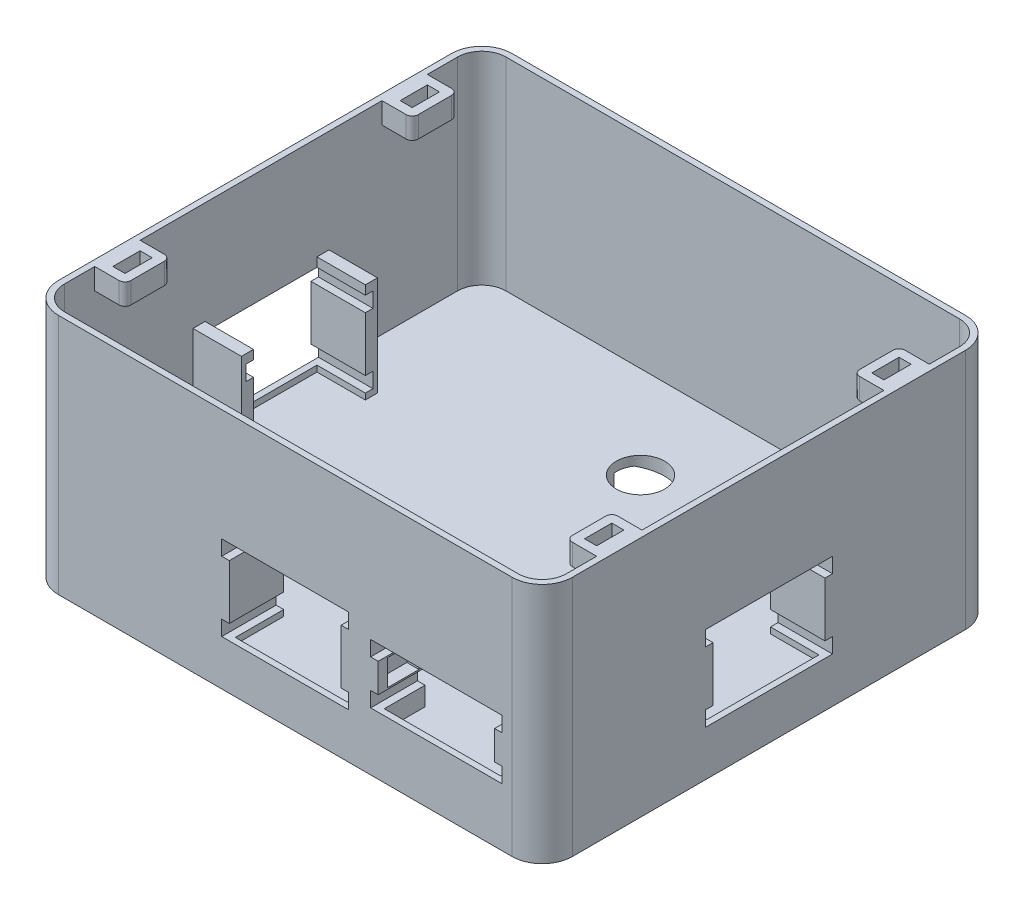
SolidWorks part; units mm, degrees
ref_plane "Front Plane" through (0, 0, 0) normal (0, 0, 1) x (1, 0, 0)
ref_plane "Top Plane" through (0, 0, 0) normal (0, 1, 0) x (1, 0, 0)
ref_plane "Right Plane" through (0, 0, 0) normal (1, 0, 0) x (0, 0, -1)
sketch "Sketch2" plane through (0, 0, 0) normal (0, 1, 0) x (1, 0, 0)
  line L1 (-85, 75) -> (85, 75)
  line L2 (-85, 75) -> (-85, -75)
  line L3 (-85, -75) -> (85, -75)
  line L4 (85, 75) -> (85, -75)
  line L5 (-85, 75) -> (85, -75) construction
  line L6 (-85, -75) -> (85, 75) construction
  point P0 (0, 0)
  dimension "D1" = 170
  dimension "D2" = 150
extrude "Boss-Extrude1" add sketch "Sketch2" along normal blind 80
fillet "Fillet1" radius 10 4 edges at (-85, 40, -75) (85, 40, -75) (85, 40, 75) (-85, 40, 75)
shell "Shell1" thickness 2
sketch "Sketch5" plane through (0, 0, 75) normal (0, 0, 1) x (1, 0, 0)
  line L1 (-18.5, 43) -> (18.5, 43)
  line L2 (-18.5, 43) -> (-18.5, 15)
  line L3 (-18.5, 15) -> (18.5, 15)
  line L4 (18.5, 43) -> (18.5, 15)
  line L5 (-18.5, 43) -> (-21, 43)
  line L6 (-21, 43) -> (-21, 38)
  line L7 (-21, 38) -> (-18.5, 38)
  line L8 (-18.5, 38) -> (-18.5, 43)
  line L9 (0, 43) -> (0, 15) construction
  line L10 (-18.5, 29) -> (18.5, 29) construction
  line L11 (-21, 20) -> (-18.5, 20)
  line L12 (-21, 15) -> (-21, 20)
  line L13 (-18.5, 15) -> (-21, 15)
  line L14 (-18.5, 20) -> (-18.5, 15)
  line L15 (21, 15) -> (21, 20)
  line L16 (18.5, 15) -> (21, 15)
  line L17 (18.5, 20) -> (18.5, 15)
  line L18 (21, 20) -> (18.5, 20)
  line L19 (21, 38) -> (18.5, 38)
  line L20 (21, 43) -> (21, 38)
  line L21 (18.5, 43) -> (21, 43)
  line L22 (18.5, 38) -> (18.5, 43)
  line L23 (-75, 13) -> (75, 13) construction
  point P4 (0, 15)
  dimension "D1" = 37
  dimension "D2" = 28
  dimension "D3" = 5
  dimension "D7" = 2.5
  dimension "D8" = 2
extrude "Cut-Extrude1" cut sketch "Sketch5" against normal up to surface (2 mm away) contours L1 L4 L3 L2 | L7 L8 L5 L6 | L12 L11 L14 L13 | L20 L19 L22 L21 | L15 L18 L17 L16 up to face at (0, 46.5, 73)
sketch "Sketch6" plane through (0, 0, 73) normal (0, 0, -1) x (-1, 0, 0)
  line L0 (18.5, 13) -> (22.5, 13)
  line L2 (-22.5, 46) -> (-22.5, 13)
  line L4 (21, 43) -> (18.5, 43)
  line L5 (21, 38) -> (21, 43)
  line L6 (18.5, 38) -> (21, 38)
  line L7 (18.5, 43) -> (18.5, 38)
  line L8 (21, 43) -> (18.5, 43)
  line L9 (21, 38) -> (21, 43)
  line L10 (18.5, 38) -> (21, 38)
  line L12 (18.5, 43) -> (-18.5, 43)
  line L13 (-18.5, 43) -> (-18.5, 15)
  line L14 (-18.5, 15) -> (18.5, 15)
  line L15 (18.5, 15) -> (18.5, 43)
  line L17 (-18.5, 46) -> (-18.5, 43)
  line L19 (18.5, 13) -> (18.5, 15)
  line L20 (-21, 38) -> (-18.5, 38)
  line L21 (-18.5, 38) -> (-18.5, 43)
  line L22 (-18.5, 43) -> (-21, 43)
  line L23 (-21, 43) -> (-21, 38)
  line L24 (-21, 38) -> (-18.5, 38)
  line L26 (-18.5, 43) -> (-21, 43)
  line L27 (-21, 43) -> (-21, 38)
  line L28 (-21, 20) -> (-21, 15)
  line L29 (-18.5, 20) -> (-21, 20)
  line L30 (-18.5, 15) -> (-18.5, 20)
  line L31 (-21, 15) -> (-18.5, 15)
  line L32 (-21, 20) -> (-21, 15)
  line L33 (-18.5, 20) -> (-21, 20)
  line L35 (-21, 15) -> (-18.5, 15)
  line L36 (21, 20) -> (18.5, 20)
  line L37 (18.5, 20) -> (18.5, 15)
  line L38 (18.5, 15) -> (21, 15)
  line L39 (21, 15) -> (21, 20)
  line L40 (21, 20) -> (18.5, 20)
  line L42 (18.5, 15) -> (21, 15)
  line L43 (21, 15) -> (21, 20)
  line L44 (22.5, 46) -> (22.5, 13)
  line L45 (-18.5, 13) -> (-22.5, 13)
  line L46 (-18.5, 38) -> (-18.5, 20)
  line L47 (18.5, 43) -> (18.5, 46)
  line L48 (18.5, 20) -> (18.5, 38)
  line L49 (-18.5, 15) -> (-18.5, 13)
  line L50 (22.5, 46) -> (18.5, 46)
  line L51 (-22.5, 46) -> (-18.5, 46)
  line L54 (21, 43) -> (-21, 43) construction
  line L55 (75, 13) -> (-75, 13) construction
  dimension "D6" = 3
  dimension "D7" = 4
  dimension "D8" = 4
  dimension "D1" = 0
  dimension "D2" = 0
  dimension "D3" = 0
  dimension "D4" = 0
  dimension "D5" = 0
extrude "Boss-Extrude2" add sketch "Sketch6" along normal blind 16
sketch "Sketch7" plane through (85, 0, 0) normal (1, 0, 0) x (0, 0, -1)
  line L0 (-65, 13) -> (65, 13) construction
  line L1 (-18.5, 43) -> (18.5, 43)
  line L2 (-18.5, 43) -> (-18.5, 15)
  line L3 (-18.5, 15) -> (18.5, 15)
  line L4 (18.5, 43) -> (18.5, 15)
  line L5 (-18.5, 43) -> (-21, 43)
  line L6 (-21, 43) -> (-21, 38)
  line L7 (-21, 38) -> (-18.5, 38)
  line L8 (-18.5, 38) -> (-18.5, 43)
  line L9 (0, 43) -> (0, 15) construction
  line L10 (-18.5, 29) -> (18.5, 29) construction
  line L11 (-21, 20) -> (-18.5, 20)
  line L12 (-21, 15) -> (-21, 20)
  line L13 (-18.5, 15) -> (-21, 15)
  line L14 (-18.5, 20) -> (-18.5, 15)
  line L15 (21, 15) -> (21, 20)
  line L16 (18.5, 15) -> (21, 15)
  line L17 (18.5, 20) -> (18.5, 15)
  line L18 (21, 20) -> (18.5, 20)
  line L19 (21, 38) -> (18.5, 38)
  line L20 (21, 43) -> (21, 38)
  line L21 (18.5, 43) -> (21, 43)
  line L22 (18.5, 38) -> (18.5, 43)
  dimension "D1" = 37
  dimension "D2" = 28
  dimension "D3" = 5
  dimension "D7" = 2.5
  dimension "D8" = 2
extrude "Cut-Extrude2" cut sketch "Sketch7" against normal blind 2 contours L1 L4 L3 L2 | L7 L8 L5 L6 | L12 L11 L14 L13 | L20 L19 L22 L21 | L15 L18 L17 L16
sketch "Sketch8" plane through (83, 0, 0) normal (-1, 0, 0) x (0, 0, 1)
  line L0 (65, 13) -> (-65, 13) construction
  line L1 (-22.5, 46) -> (-18.5, 46)
  line L2 (-22.5, 46) -> (-22.5, 13)
  line L3 (-22.5, 13) -> (-18.5, 13)
  line L4 (21, 43) -> (18.5, 43)
  line L5 (21, 38) -> (21, 43)
  line L6 (18.5, 38) -> (21, 38)
  line L7 (18.5, 43) -> (18.5, 38)
  line L8 (21, 43) -> (18.5, 43)
  line L9 (21, 38) -> (21, 43)
  line L10 (18.5, 38) -> (21, 38)
  line L20 (-21, 38) -> (-18.5, 38)
  line L21 (-18.5, 38) -> (-18.5, 43)
  line L22 (-18.5, 43) -> (-21, 43)
  line L23 (-21, 43) -> (-21, 38)
  line L24 (-21, 38) -> (-18.5, 38)
  line L26 (-18.5, 43) -> (-21, 43)
  line L27 (-21, 43) -> (-21, 38)
  line L28 (-21, 20) -> (-21, 15)
  line L29 (-18.5, 20) -> (-21, 20)
  line L30 (-18.5, 15) -> (-18.5, 20)
  line L31 (-21, 15) -> (-18.5, 15)
  line L32 (-21, 20) -> (-21, 15)
  line L33 (-18.5, 20) -> (-21, 20)
  line L35 (-21, 15) -> (-18.5, 15)
  line L36 (21, 20) -> (18.5, 20)
  line L37 (18.5, 20) -> (18.5, 15)
  line L38 (18.5, 15) -> (21, 15)
  line L39 (21, 15) -> (21, 20)
  line L40 (21, 20) -> (18.5, 20)
  line L42 (18.5, 15) -> (21, 15)
  line L43 (21, 15) -> (21, 20)
  line L44 (-18.5, 46) -> (-18.5, 43)
  line L46 (-18.5, 38) -> (-18.5, 20) construction
  line L47 (21, 43) -> (-21, 43) construction
  line L48 (-18.5, 38) -> (-18.5, 20)
  line L49 (-18.5, 15) -> (-18.5, 13)
  line L50 (18.5, 38) -> (18.5, 20) construction
  line L51 (18.5, 46) -> (22.5, 46)
  line L52 (18.5, 46) -> (18.5, 43)
  line L53 (18.5, 13) -> (22.5, 13)
  line L54 (22.5, 46) -> (22.5, 13)
  line L55 (18.5, 38) -> (18.5, 20)
  line L56 (18.5, 15) -> (18.5, 13)
  dimension "D6" = 4
  dimension "D7" = 4
  dimension "D2" = 3
  dimension "D1" = 0
  dimension "D3" = 0
  dimension "D4" = 0
  dimension "D5" = 0
extrude "Boss-Extrude3" add sketch "Sketch8" along normal blind 16
sketch "Sketch10" plane through (-85, 0, 0) normal (-1, 0, 0) x (0, 0, 1)
  line L1 (-18.5, 43) -> (18.5, 43)
  line L2 (-18.5, 43) -> (-18.5, 15)
  line L3 (-18.5, 15) -> (18.5, 15)
  line L4 (18.5, 43) -> (18.5, 15)
  line L5 (-18.5, 43) -> (-21, 43)
  line L6 (-21, 43) -> (-21, 38)
  line L7 (-21, 38) -> (-18.5, 38)
  line L8 (-18.5, 38) -> (-18.5, 43)
  line L9 (0, 43) -> (0, 15) construction
  line L10 (-18.5, 29) -> (18.5, 29) construction
  line L11 (-21, 20) -> (-18.5, 20)
  line L12 (-21, 15) -> (-21, 20)
  line L13 (-18.5, 15) -> (-21, 15)
  line L14 (-18.5, 20) -> (-18.5, 15)
  line L15 (21, 15) -> (21, 20)
  line L16 (18.5, 15) -> (21, 15)
  line L17 (18.5, 20) -> (18.5, 15)
  line L18 (21, 20) -> (18.5, 20)
  line L19 (21, 38) -> (18.5, 38)
  line L20 (21, 43) -> (21, 38)
  line L21 (18.5, 43) -> (21, 43)
  line L22 (18.5, 38) -> (18.5, 43)
  line L23 (-65, 13) -> (65, 13) construction
  dimension "D1" = 37
  dimension "D2" = 28
  dimension "D3" = 5
  dimension "D7" = 2.5
  dimension "D8" = 2
extrude "Cut-Extrude4" cut sketch "Sketch10" against normal blind 2 contours L1 L4 L3 L2 | L7 L8 L5 L6 | L12 L11 L14 L13 | L20 L19 L22 L21 | L15 L18 L17 L16
sketch "Sketch11" plane through (-83, 0, 0) normal (1, 0, 0) x (0, 0, -1)
  line L1 (-18.5, 38) -> (-18.5, 20) construction
  line L2 (-18.5, 46) -> (-22.5, 46)
  line L3 (-18.5, 46) -> (-18.5, 43)
  line L4 (21, 43) -> (18.5, 43)
  line L5 (21, 38) -> (21, 43)
  line L6 (18.5, 38) -> (21, 38)
  line L7 (18.5, 43) -> (18.5, 38)
  line L8 (21, 43) -> (18.5, 43)
  line L9 (21, 38) -> (21, 43)
  line L10 (18.5, 38) -> (21, 38)
  line L20 (-21, 38) -> (-18.5, 38)
  line L21 (-18.5, 38) -> (-18.5, 43)
  line L22 (-18.5, 43) -> (-21, 43)
  line L23 (-21, 43) -> (-21, 38)
  line L24 (-21, 38) -> (-18.5, 38)
  line L26 (-18.5, 43) -> (-21, 43)
  line L27 (-21, 43) -> (-21, 38)
  line L28 (-21, 20) -> (-21, 15)
  line L29 (-18.5, 20) -> (-21, 20)
  line L30 (-18.5, 15) -> (-18.5, 20)
  line L31 (-21, 15) -> (-18.5, 15)
  line L32 (-21, 20) -> (-21, 15)
  line L33 (-18.5, 20) -> (-21, 20)
  line L35 (-21, 15) -> (-18.5, 15)
  line L36 (21, 20) -> (18.5, 20)
  line L37 (18.5, 20) -> (18.5, 15)
  line L38 (18.5, 15) -> (21, 15)
  line L39 (21, 15) -> (21, 20)
  line L40 (21, 20) -> (18.5, 20)
  line L42 (18.5, 15) -> (21, 15)
  line L43 (21, 15) -> (21, 20)
  line L44 (-18.5, 13) -> (-22.5, 13)
  line L45 (-22.5, 46) -> (-22.5, 13)
  line L46 (65, 13) -> (-65, 13) construction
  line L47 (21, 43) -> (-21, 43) construction
  line L48 (-18.5, 38) -> (-18.5, 20)
  line L49 (-18.5, 15) -> (-18.5, 13)
  line L50 (18.5, 38) -> (18.5, 20) construction
  line L51 (18.5, 46) -> (22.5, 46)
  line L52 (18.5, 46) -> (18.5, 43)
  line L53 (18.5, 13) -> (22.5, 13)
  line L54 (22.5, 46) -> (22.5, 13)
  line L55 (18.5, 38) -> (18.5, 20)
  line L56 (18.5, 15) -> (18.5, 13)
  dimension "D2" = 4
  dimension "D6" = 3
  dimension "D7" = 4
  dimension "D1" = 0
  dimension "D3" = 0
  dimension "D4" = 0
  dimension "D5" = 0
extrude "Boss-Extrude4" add sketch "Sketch11" along normal blind 16
sketch "Sketch13" plane through (0, 0, 75) normal (0, 0, 1) x (1, 0, 0)
  line L0 (-18.5, 29) -> (18.5, 29) construction
  line L1 (-18.5, 29) -> (18.5, 29) construction
  line L2 (30.75, 38.8) -> (28.25, 38.8)
  line L3 (30.75, 38.8) -> (69.25, 38.8)
  line L4 (30.75, 38.8) -> (30.75, 19.2)
  line L5 (30.75, 19.2) -> (69.25, 19.2)
  line L6 (69.25, 38.8) -> (69.25, 19.2)
  line L7 (28.25, 38.8) -> (28.25, 33.8)
  line L8 (28.25, 33.8) -> (30.75, 33.8)
  line L9 (30.75, 38.8) -> (30.75, 33.8)
  line L10 (50, 38.8) -> (50, 19.2) construction
  line L11 (30.75, 19.2) -> (28.25, 19.2)
  line L12 (28.25, 19.2) -> (28.25, 24.2)
  line L13 (28.25, 24.2) -> (30.75, 24.2)
  line L14 (30.75, 19.2) -> (30.75, 24.2)
  line L15 (69.25, 19.2) -> (69.25, 24.2)
  line L16 (71.75, 24.2) -> (69.25, 24.2)
  line L17 (71.75, 19.2) -> (71.75, 24.2)
  line L18 (69.25, 19.2) -> (71.75, 19.2)
  line L19 (69.25, 38.8) -> (71.75, 38.8)
  line L20 (71.75, 38.8) -> (71.75, 33.8)
  line L21 (71.75, 33.8) -> (69.25, 33.8)
  line L22 (69.25, 38.8) -> (69.25, 33.8)
  point P6 (30.75, 29)
  point P7 (50, 19.2)
  dimension "D1" = 19.6
  dimension "D2" = 38.5
  dimension "D3" = 50
  dimension "D4" = 5
  dimension "D8" = 2.5
extrude "Cut-Extrude5" cut sketch "Sketch13" against normal up to surface (2 mm away) contours L3 L6 L5 L4 | L7 L8 L9 L2 | L12 L13 L14 L11 | L17 L16 L15 L18 | L20 L21 L22 L19 up to face at (0, 40.1667, 73)
sketch "Sketch14" plane through (0, 0, 73) normal (0, 0, -1) x (-1, 0, 0)
  line L0 (-22.5, 13) -> (-75, 13) construction
  line L1 (-69.25, 41.8) -> (-73.25, 41.8)
  line L2 (-69.25, 41.8) -> (-69.25, 38.8)
  line L3 (-69.25, 13) -> (-73.25, 13)
  line L6 (-73.25, 41.8) -> (-73.25, 13)
  line L12 (-28.25, 38.8) -> (-30.75, 38.8)
  line L13 (-28.25, 33.8) -> (-28.25, 38.8)
  line L14 (-30.75, 33.8) -> (-28.25, 33.8)
  line L15 (-30.75, 38.8) -> (-30.75, 33.8)
  line L16 (-28.25, 38.8) -> (-30.75, 38.8)
  line L17 (-28.25, 33.8) -> (-28.25, 38.8)
  line L18 (-30.75, 33.8) -> (-28.25, 33.8)
  line L20 (-69.25, 38.8) -> (-71.75, 38.8)
  line L21 (-71.75, 38.8) -> (-71.75, 33.8)
  line L22 (-71.75, 33.8) -> (-69.25, 33.8)
  line L23 (-69.25, 33.8) -> (-69.25, 38.8)
  line L24 (-69.25, 38.8) -> (-71.75, 38.8)
  line L25 (-71.75, 38.8) -> (-71.75, 33.8)
  line L26 (-71.75, 33.8) -> (-69.25, 33.8)
  line L28 (-69.25, 19.2) -> (-69.25, 24.2)
  line L29 (-69.25, 24.2) -> (-71.75, 24.2)
  line L30 (-71.75, 24.2) -> (-71.75, 19.2)
  line L31 (-71.75, 19.2) -> (-69.25, 19.2)
  line L33 (-69.25, 24.2) -> (-71.75, 24.2)
  line L34 (-71.75, 24.2) -> (-71.75, 19.2)
  line L35 (-71.75, 19.2) -> (-69.25, 19.2)
  line L36 (-28.25, 19.2) -> (-28.25, 24.2)
  line L37 (-28.25, 24.2) -> (-30.75, 24.2)
  line L38 (-30.75, 24.2) -> (-30.75, 19.2)
  line L39 (-30.75, 19.2) -> (-28.25, 19.2)
  line L40 (-28.25, 19.2) -> (-28.25, 24.2)
  line L41 (-28.25, 24.2) -> (-30.75, 24.2)
  line L43 (-30.75, 19.2) -> (-28.25, 19.2)
  line L44 (-28.25, 38.8) -> (-71.75, 38.8) construction
  line L45 (-30.75, 41.8) -> (-26.75, 41.8)
  line L46 (-30.75, 41.8) -> (-30.75, 38.8)
  line L47 (-30.75, 13) -> (-26.75, 13)
  line L48 (-26.75, 41.8) -> (-26.75, 13)
  line L49 (-69.25, 33.8) -> (-69.25, 24.2) construction
  line L50 (-30.75, 33.8) -> (-30.75, 24.2) construction
  line L51 (-69.25, 33.8) -> (-69.25, 24.2)
  line L52 (-69.25, 19.2) -> (-69.25, 13)
  line L53 (-30.75, 33.8) -> (-30.75, 24.2)
  line L54 (-30.75, 19.2) -> (-30.75, 13)
  dimension "D1" = 3
  dimension "D6" = 4
  dimension "D7" = 4
  dimension "D2" = 0
  dimension "D3" = 0
  dimension "D4" = 0
  dimension "D5" = 0
extrude "Boss-Extrude5" add sketch "Sketch14" along normal blind 13.5
sketch "Sketch15" plane through (26.75, 0, 0) normal (-1, 0, 0) x (0, 0, 1)
  line L4 (59.5, 13) -> (59.5, 41.8) construction
  line L5 (73, 13) -> (73, 41.8) construction
  line L6 (59.5, 41.8) -> (59.5, 13) construction
  line L7 (59.5, 33.8) -> (75, 33.8) construction
  line L8 (59.5, 24.2) -> (75, 24.2) construction
  line L12 (72, 24.7) -> (72, 33.3)
  line L13 (72, 33.3) -> (61.5, 33.3)
  line L14 (61.5, 33.3) -> (61.5, 24.7)
  line L15 (61.5, 24.7) -> (72, 24.7)
  dimension "D1" = 2
  dimension "D2" = 1
  dimension "D3" = 0.5
  dimension "D4" = 0.5
extrude "Cut-Extrude6" cut sketch "Sketch15" against normal up to surface (4 mm away) up to face at (30.75, 29, 67.25)
sketch "Sketch18" plane through (0, 0, 0) normal (1, 0, 0) x (0, 0, -1)
  line L0 (0, 0) -> (0, 10) construction
  line L2 (-22.5, 13) -> (-65, 13) construction
  line L3 (-42.5, 0) -> (-70, 0)
  line L4 (-70, 0) -> (-47.5, 10)
  line L5 (-47.5, 10) -> (-42.5, 10)
  line L6 (-42.5, 10) -> (-42.5, 0)
  line L7 (65, 0) -> (-65, 0) construction
  dimension "D1" = 3
  dimension "D2" = 70
  dimension "D3" = 5
  dimension "D4" = 42.5
revolve "Cut-Revolve1" cut sketch "Sketch18" angle 360 about L0
sketch "Sketch20" plane through (0, 0, 0) normal (0, -1, 0) x (1, 0, 0)
  circle A0 centre (0, -42.5) radius 8
  circle A1 centre (0, 0) radius 42.5 construction
  circle A2 centre (0, 0) radius 42.5 construction
  dimension "D1" = 16
extrude "Cut-Extrude8" cut sketch "Sketch20" against normal up to surface (13 mm away) up to face at (10, 13, 26.25)
sketch "Sketch22" plane through (0, 0, 0) normal (0, -1, 0) x (1, 0, 0)
  line L0 (-85, 65) -> (85, 65) construction
  line L1 (-82.0711, 72.0711) -> (-67.9289, 57.9289) construction
  line L2 (44, 0) -> (-44, 0) construction
  line L3 (0, -44) -> (0, 44) construction
  circle A0 centre (-67.9289, 57.9289) radius 3
  arc A5 (-75, 75) -> (-85, 65) centre (-75, 65) ccw construction
  circle A6 centre (-67.9289, -57.9289) radius 3
  circle A7 centre (67.9289, -57.9289) radius 3
  circle A8 centre (67.9289, 57.9289) radius 3
  point P10 (-82.0711, 72.0711)
  dimension "D3" = 6
  dimension "D1" = 45
  dimension "D2" = 20
extrude "Cut-Extrude9" cut sketch "Sketch22" against normal blind 5
sketch "Sketch23" plane through (0, 13, 0) normal (0, 1, 0) x (1, 0, 0)
  line L0 (-83, 65) -> (-83, 22.5) construction
  line L1 (-83, 55) -> (-73, 55)
  line L2 (-83, 55) -> (-83, 40)
  line L3 (-83, 40) -> (-73, 40)
  line L4 (-73, 55) -> (-73, 40)
  dimension "D1" = 10
  dimension "D2" = 15
  dimension "D3" = 40
extrude "Boss-Extrude6" add sketch "Sketch23" along normal up to surface (7 mm away) from offset 60 up to face at (0, 80, 0)
sketch "Sketch24" plane through (0, 80, 0) normal (0, 1, 0) x (1, 0, 0)
  line L8 (-76, 52) -> (-80, 52)
  line L9 (-76, 43) -> (-76, 52)
  line L10 (-80, 43) -> (-76, 43)
  line L11 (-80, 52) -> (-80, 43)
  line L12 (-76, 52) -> (-80, 52)
  line L13 (-76, 43) -> (-76, 52)
  line L14 (-80, 43) -> (-76, 43)
  line L15 (-80, 52) -> (-80, 43)
  dimension "D1" = 3
extrude "Cut-Extrude10" cut sketch "Sketch24" against normal blind 5
mirror "Mirror1" about plane through (0, 0, 0) normal (1, 0, 0) of "Boss-Extrude6", "Cut-Extrude10" second plane through (0, 0, 0) second plane normal (0, 0, 1)
fillet "Fillet2" radius 2 8 edges at (-73, 76.5, -40) (-73, 76.5, -55) (-73, 76.5, 40) (-73, 76.5, 55) (73, 76.5, -40) (73, 76.5, -55) (73, 76.5, 40) (73, 76.5, 55)
sketch "Sketch25" plane through (0, 0, 75) normal (0, 0, 1) x (1, 0, 0)
  line L0 (-69, 74) -> (-69, 19)
  line L1 (-69, 19) -> (-33.5, 19)
  line L2 (-33.5, 19) -> (-33.5, 74)
  line L3 (-27.5, 49) -> (27.5, 49)
  line L4 (27.5, 49) -> (27.5, 74)
  line L5 (27.5, 74) -> (-27.5, 74)
  line L6 (-33.5, 74) -> (-69, 74)
  line L7 (33.5, 49) -> (69, 49)
  line L8 (69, 49) -> (69, 74)
  line L9 (69, 74) -> (33.5, 74)
  line L10 (33.5, 74) -> (33.5, 49)
  line L11 (-27.5, 74) -> (-27.5, 49)
  line L12 (-75, 80) -> (75, 80) construction
  line L13 (-21, 43) -> (21, 43) construction
  line L14 (75, 0) -> (75, 80) construction
  line L15 (-75, 80) -> (-75, 0) construction
  line L17 (-75, 13) -> (-22.5, 13) construction
  point P4 (0, 49)
  point P12 (27.7533, 73.6813)
  point P26 (-36.3226, 18.6232)
  point P27 (-33.3398, 19)
  dimension "D1" = 6
  dimension "D2" = 6
  dimension "D3" = 6
  dimension "D4" = 6
  dimension "D5" = 6
  dimension "D6" = 6
  dimension "D7" = 6
  dimension "D8" = 55
sketch "Sketch26" plane through (83, 0, 0) normal (-1, 0, 0) x (0, 0, 1)
  line L0 (-37, 19) -> (-25.5, 19)
  line L1 (-25.5, 19) -> (-25.5, 74)
  line L2 (-25.5, 74) -> (-37, 74)
  line L3 (-37, 74) -> (-37, 19)
  line L4 (-19.5, 74) -> (-19.5, 52)
  line L5 (-19.5, 52) -> (19.5, 52)
  line L6 (19.5, 52) -> (19.5, 74)
  line L7 (19.5, 74) -> (-19.5, 74)
  line L8 (25.5, 74) -> (25.5, 19)
  line L9 (25.5, 19) -> (37, 19)
  line L10 (37, 19) -> (37, 74)
  line L11 (37, 74) -> (25.5, 74)
  line L12 (-22.5, 13) -> (-65, 13) construction
  line L15 (-22.5, 46) -> (-22.5, 13) construction
  line L18 (-18.5, 46) -> (-22.5, 46) construction
  line L19 (40, 80) -> (-40, 80) construction
  line L20 (-40, 80) -> (-40, 73) construction
  line L21 (40, 80) -> (40, 73) construction
  line L23 (-59, 67) -> (-43, 67)
  line L24 (-59, 67) -> (-59, 19)
  line L25 (-59, 19) -> (-43, 19)
  line L26 (-43, 67) -> (-43, 19)
  line L27 (43, 67) -> (59, 67)
  line L28 (43, 67) -> (43, 19)
  line L29 (43, 19) -> (59, 19)
  line L30 (59, 67) -> (59, 19)
  line L31 (-65, 13) -> (-65, 80) construction
  line L32 (55, 73) -> (40, 73) construction
  line L33 (65, 80) -> (65, 13) construction
  line L34 (-55, 73) -> (-40, 73) construction
  point P16 (0, 52)
  dimension "D1" = 6
  dimension "D2" = 6
  dimension "D3" = 6
  dimension "D4" = 6
  dimension "D5" = 3
  dimension "D6" = 3
  dimension "D7" = 3
  dimension "D8" = 6
  dimension "D9" = 6
  dimension "D10" = 6
  dimension "D11" = 6
  dimension "D12" = 6
  dimension "D13" = 6
  dimension "D14" = 6
sketch "Sketch29" plane through (-85, 0, 0) normal (-1, 0, 0) x (0, 0, 1)
  line L4 (25.5, 74) -> (25.5, 19)
  line L5 (25.5, 19) -> (37, 19)
  line L6 (37, 19) -> (37, 74)
  line L7 (37, 74) -> (25.5, 74)
  line L8 (25.5, 74) -> (25.5, 19)
  line L9 (25.5, 19) -> (37, 19)
  line L10 (37, 19) -> (37, 74)
  line L11 (37, 74) -> (25.5, 74)
  line L12 (-19.5, 74) -> (-19.5, 52)
  line L13 (-19.5, 52) -> (19.5, 52)
  line L14 (19.5, 52) -> (19.5, 74)
  line L15 (19.5, 74) -> (-19.5, 74)
  line L16 (-19.5, 74) -> (-19.5, 52)
  line L17 (-19.5, 52) -> (19.5, 52)
  line L18 (19.5, 52) -> (19.5, 74)
  line L19 (19.5, 74) -> (-19.5, 74)
  line L20 (-37, 19) -> (-25.5, 19)
  line L21 (-25.5, 19) -> (-25.5, 74)
  line L22 (-25.5, 74) -> (-37, 74)
  line L23 (-37, 74) -> (-37, 19)
  line L24 (-37, 19) -> (-25.5, 19)
  line L25 (-25.5, 19) -> (-25.5, 74)
  line L26 (-25.5, 74) -> (-37, 74)
  line L27 (-37, 74) -> (-37, 19)
  line L28 (-43, 67) -> (-59, 67)
  line L29 (-43, 19) -> (-43, 67)
  line L30 (-59, 19) -> (-43, 19)
  line L31 (-59, 67) -> (-59, 19)
  line L32 (-43, 67) -> (-59, 67)
  line L33 (-43, 19) -> (-43, 67)
  line L34 (-59, 19) -> (-43, 19)
  line L35 (-59, 67) -> (-59, 19)
  line L36 (59, 67) -> (43, 67)
  line L37 (43, 67) -> (43, 19)
  line L38 (43, 19) -> (59, 19)
  line L39 (59, 19) -> (59, 67)
  line L40 (59, 67) -> (43, 67)
  line L41 (43, 67) -> (43, 19)
  line L42 (43, 19) -> (59, 19)
  line L43 (59, 19) -> (59, 67)
  dimension "D1" = 0
  dimension "D2" = 0
  dimension "D3" = 0
  dimension "D4" = 0
  dimension "D5" = 0
sketch "Sketch27" plane through (0, 0, -75) normal (0, 0, -1) x (-1, 0, 0)
  line L0 (75, 0) -> (75, 80) construction
  line L1 (-69, 74) -> (-41, 74)
  line L2 (-69, 74) -> (-69, 19)
  line L3 (-69, 19) -> (-41, 19)
  line L4 (-41, 74) -> (-41, 19)
  line L5 (-35, 74) -> (35, 74)
  line L6 (-35, 74) -> (-35, 19)
  line L7 (-35, 19) -> (35, 19)
  line L8 (35, 74) -> (35, 19)
  line L9 (41, 74) -> (69, 74)
  line L10 (41, 74) -> (41, 19)
  line L11 (41, 19) -> (69, 19)
  line L12 (69, 74) -> (69, 19)
  line L13 (-75, 80) -> (-75, 0) construction
  line L14 (-75, 80) -> (75, 80) construction
  line L15 (-75, 13) -> (75, 13) construction
  point P20 (0, 19)
  dimension "D1" = 6
  dimension "D2" = 6
  dimension "D3" = 6
  dimension "D4" = 6
  dimension "D5" = 6
  dimension "D6" = 6
  dimension "D7" = 70
sketch "Sketch28" plane through (0, 0, 0) normal (0, -1, 0) x (1, 0, 0)
  arc A2 (10.9512, -41.4647) -> (-10.9512, -41.4647) centre (0, -42.5) ccw
  arc A3 (10.1172, -38.1824) -> (-10.1172, -38.1824) centre (0, -42.5) ccw
  arc A6 (7.4023, -38.8002) -> (-7.4023, -38.8002) centre (0, 0) ccw
  arc A7 (10.1172, -38.1824) -> (-10.1172, -38.1824) centre (0, 0) ccw
  dimension "D1" = 3
  dimension "D2" = 3
extrude "Cut-Extrude14" cut sketch "Sketch28" against normal up to surface (10 mm away) up to face at (0, 10, 0.2422)
sketch "Sketch30" plane through (0, 0, 0) normal (0, -1, 0) x (1, 0, 0)
  line L0 (12.0416, -72) -> (75, -72)
  line L1 (-12.0416, 72) -> (-75, 72)
  line L8 (-82, 65) -> (-82, -65)
  line L9 (-75, -72) -> (75, -72)
  line L10 (82, -65) -> (82, 65)
  line L11 (75, 72) -> (-75, 72)
  line L12 (-82, 65) -> (-82, -65)
  line L13 (-75, -72) -> (-12.0416, -72)
  line L14 (82, -65) -> (82, 65)
  line L15 (75, 72) -> (12.0416, 72)
  circle A2 centre (0, 0) radius 73
  arc A3 (12.0416, -72) -> (12.0416, 72) centre (0, 0) ccw
  circle A5 centre (67.9289, 57.9289) radius 6
  circle A6 centre (67.9289, 57.9289) radius 6
  arc A8 (-82, -65) -> (-75, -72) centre (-75, -65) ccw
  arc A9 (75, -72) -> (82, -65) centre (75, -65) ccw
  arc A10 (82, 65) -> (75, 72) centre (75, 65) ccw
  arc A11 (-75, 72) -> (-82, 65) centre (-75, 65) ccw
  arc A12 (-82, -65) -> (-75, -72) centre (-75, -65) ccw
  arc A13 (75, -72) -> (82, -65) centre (75, -65) ccw
  arc A14 (82, 65) -> (75, 72) centre (75, 65) ccw
  arc A15 (-75, 72) -> (-82, 65) centre (-75, 65) ccw
  circle A16 centre (67.9289, -57.9289) radius 6
  circle A17 centre (67.9289, -57.9289) radius 6
  arc A18 (-12.0416, 72) -> (-12.0416, -72) centre (0, 0) ccw
  circle A19 centre (-67.9289, -57.9289) radius 6
  circle A20 centre (-67.9289, -57.9289) radius 6
  circle A34 centre (-67.9289, 57.9289) radius 6
  circle A35 centre (-67.9289, 57.9289) radius 6
  dimension "D1" = 3
  dimension "D2" = 3
  dimension "D3" = 3
  dimension "D4" = 3
  dimension "D5" = 3
  dimension "D6" = 3
extrude "Cut-Extrude16" cut sketch "Sketch30" against normal offset from surface (10 mm away) 3 up to face at (0, 13, -34.5)
